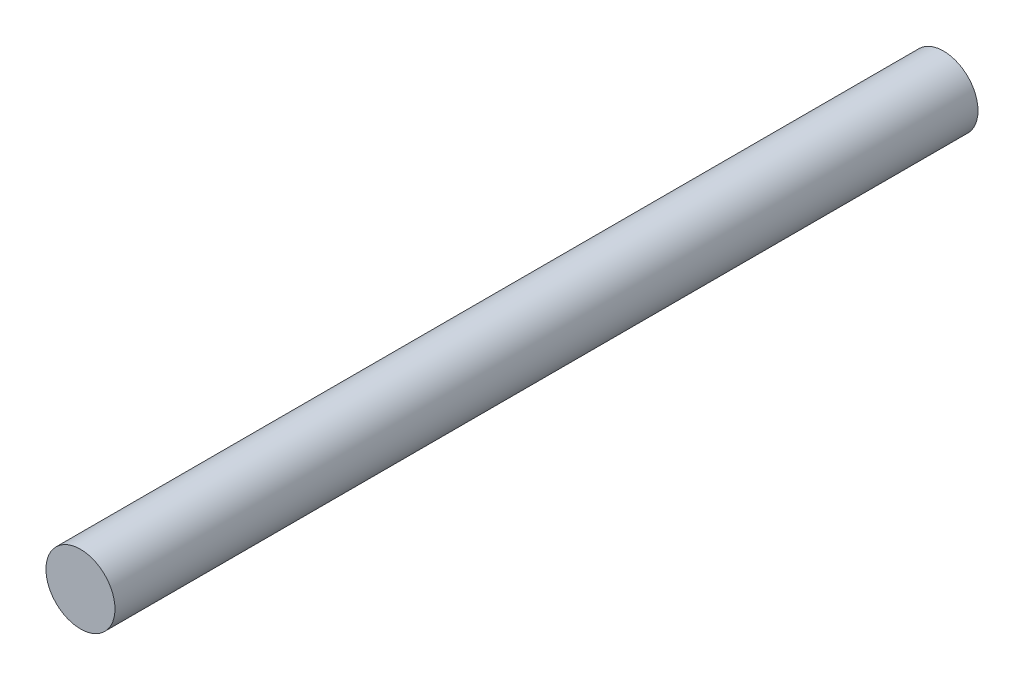
SolidWorks part; units mm, degrees
ref_plane "前视基准面" through (0, 0, 0) normal (0, 0, 1) x (1, 0, 0)
ref_plane "上视基准面" through (0, 0, 0) normal (0, 1, 0) x (1, 0, 0)
ref_plane "右视基准面" through (0, 0, 0) normal (1, 0, 0) x (0, 0, -1)
sketch "草图1" plane through (0, 0, 0) normal (0, 0, 1) x (1, 0, 0)
  circle A0 centre (0, 0) radius 2.6
  dimension "D1" = 5.2
extrude "凸台-拉伸4" add sketch "草图1" along normal blind 65
